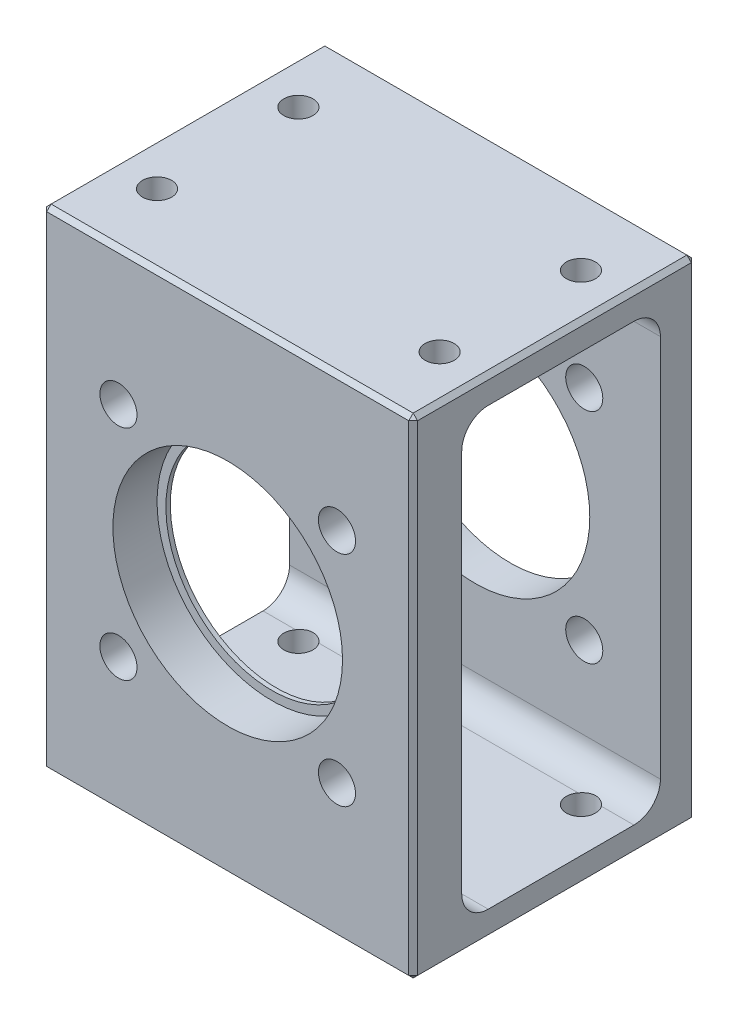
SolidWorks part; units mm, degrees
ref_plane "前视基准面" through (0, 0, 0) normal (0, 0, 1) x (1, 0, 0)
ref_plane "上视基准面" through (0, 0, 0) normal (0, 1, 0) x (1, 0, 0)
ref_plane "右视基准面" through (0, 0, 0) normal (1, 0, 0) x (0, 0, -1)
sketch "草图1" plane through (0, 0, 0) normal (0, 1, 0) x (1, 0, 0)
  line L1 (-21, 16) -> (21, 16)
  line L2 (-21, 16) -> (-21, -16)
  line L3 (-21, -16) -> (21, -16)
  line L4 (21, 16) -> (21, -16)
  line L5 (-21, 16) -> (21, -16) construction
  line L6 (-21, -16) -> (21, 16) construction
  point P0 (0, 0)
  dimension "D1" = 42
  dimension "D2" = 32
extrude "凸台-拉伸1" add sketch "草图1" along normal mid plane 55.4
sketch "草图2" plane through (0, 0, 16) normal (0, 0, 1) x (1, 0, 0)
  circle A0 centre (0, 0) radius 13
  dimension "D1" = 26
extrude "切除-拉伸1" cut sketch "草图2" against normal through all
sketch "草图3" plane through (21, 0, 0) normal (1, 0, 0) x (0, 0, -1)
  line L0 (16, 27.7) -> (16, -27.7) construction
  line L1 (-16, -27.7) -> (16, -27.7) construction
  line L2 (-16, 27.7) -> (16, 27.7) construction
  line L3 (-16, 27.7) -> (-16, -27.7) construction
  line L12 (-10.5, -24.7) -> (12, -24.7)
  line L13 (12, -24.7) -> (12, 24.7)
  line L14 (12, 24.7) -> (-10.5, 24.7)
  line L15 (-10.5, 24.7) -> (-10.5, -24.7)
  dimension "D1" = 4
  dimension "D2" = 3
  dimension "D3" = 3
  dimension "D4" = 5.5
extrude "切除-拉伸2" cut sketch "草图3" against normal through all
sketch "草图6" plane through (0, 0, 16) normal (0, 0, 1) x (1, 0, 0)
  line L0 (0, 0) -> (41.7628, 0) construction
  line L1 (0, 0) -> (0, 41.7628) construction
  line L2 (0, 0) -> (20.3774, 20.3774) construction
  circle A0 centre (12.3744, 12.3744) radius 2.1
  circle A1 centre (-12.3744, 12.3744) radius 2.1
  circle A2 centre (12.3744, -12.3744) radius 2.1
  circle A3 centre (-12.3744, -12.3744) radius 2.1
  dimension "D1" = 35
  dimension "D2" = 4.2
extrude "切除-拉伸4" cut sketch "草图6" against normal blind 50
sketch "草图7" plane through (0, 0, 10.5) normal (0, 0, -1) x (-1, 0, 0)
  circle A0 centre (0, 0) radius 13
  circle A1 centre (0, 0) radius 12
  dimension "D1" = 26
  dimension "D2" = 24
extrude "凸台-拉伸2" add sketch "草图7" against normal blind 0.5
fillet "圆角2" radius 3 4 edges at (0, -24.7, -12) (0, -24.7, 10.5) (0, 24.7, 10.5) (0, 24.7, -12)
sketch "草图4" plane through (0, 27.7, 0) normal (0, 1, 0) x (1, 0, 0)
  line L0 (-36.4382, 0) -> (40.0175, 0) construction
  line L1 (0, 31.9819) -> (0, -25.3448) construction
  circle A0 centre (-16, 8) radius 1.25
  circle A1 centre (16, 8) radius 1.25
  circle A2 centre (-16, -8) radius 1.25
  circle A3 centre (16, -8) radius 1.25
  dimension "D1" = 2.5
  dimension "D2" = 16
  dimension "D3" = 32
extrude "切除-拉伸3" cut sketch "草图4" against normal blind 7
mirror "镜向1" about plane through (0, 0, 0) normal (0, 1, 0) of "切除-拉伸3"
chamfer "倒角1" distance 0.5 angle 45 12 edges at (21, -27.7, 0) (-21, -27.7, 0) (-21, 27.7, 0) (-21, 0, 16) (0, -27.7, 16) (21, 0, 16) (0, 27.7, 16) (21, 27.7, 0) (-21, 0, -16) (0, -27.7, -16) (21, 0, -16) (0, 27.7, -16)
hole_wizard "M4 螺纹孔1" positions "草图10" profile "草图11" tap size "M4" standard "GB" end condition through all
sketch "草图10" plane through (0, 27.7, 0) normal (0, 1, 0) x (1, 0, 0)
  point P0 (16, -8)
  point P3 (16, 8)
  point P6 (-16, 8)
  point P9 (-16, -8)
sketch "草图11" plane through (16, 27.7, 8) normal (1, 0, 0) x (0, 0, 1)
  line L0 (0, 0) -> (0, 55.4)
  line L1 (0, 55.4) -> (1.65, 55.4)
  line L2 (1.65, 55.4) -> (1.65, 0)
  line L5 (1.65, 0) -> (0, 0)
  line L11 (0, -6.35) -> (0, 107.95) construction
  dimension "通孔螺纹孔钻头直径" = 3.3
  dimension "通孔螺纹孔钻头深度" = 55.4
cosmetic thread "孔螺蚊线1" parameters "D2"=4
cosmetic thread "孔螺蚊线2" parameters "D2"=4
cosmetic thread "孔螺蚊线3" parameters "D2"=4
cosmetic thread "孔螺蚊线4" parameters "D2"=4
